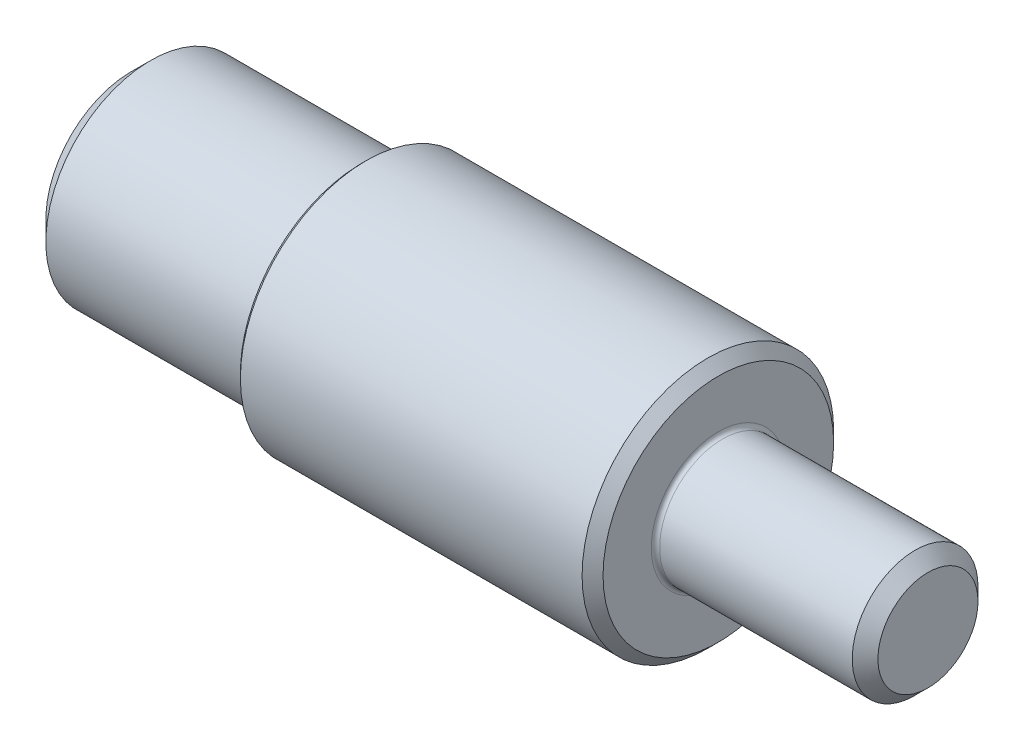
SolidWorks part; units mm, degrees
ref_plane "Front Plane" through (0, 0, 0) normal (0, 0, 1) x (1, 0, 0)
ref_plane "Top Plane" through (0, 0, 0) normal (0, 1, 0) x (1, 0, 0)
ref_plane "Right Plane" through (0, 0, 0) normal (1, 0, 0) x (0, 0, -1)
sketch "Sketch1" plane through (0, 0, 0) normal (0, 0, 1) x (1, 0, 0)
  line L0 (-11, 4.08) -> (-11, 0)
  line L1 (-11, 0) -> (27, 0)
  line L2 (27, 0) -> (27, 2.3865)
  line L3 (27, 2.3865) -> (26.3865, 3)
  line L4 (26.3865, 3) -> (17.2, 3)
  line L5 (17, 3.2) -> (17, 5.5)
  line L6 (17, 5.5) -> (16.5, 6)
  line L7 (16.5, 6) -> (0.2, 6)
  line L8 (0.2, 6) -> (0, 5.8)
  line L9 (0, 5.8) -> (0, 5.2)
  line L10 (-0.2, 5) -> (-10.08, 5)
  line L11 (-10.08, 5) -> (-11, 4.08)
  line L12 (-11, 0) -> (27, 0) construction
  arc A0 (17.2, 3) -> (17, 3.2) centre (17.2, 3.2) cw
  arc A1 (0, 5.2) -> (-0.2, 5) centre (-0.2, 5.2) cw
revolve "Revolve1" add sketch "Sketch1" angle 360 about L12
